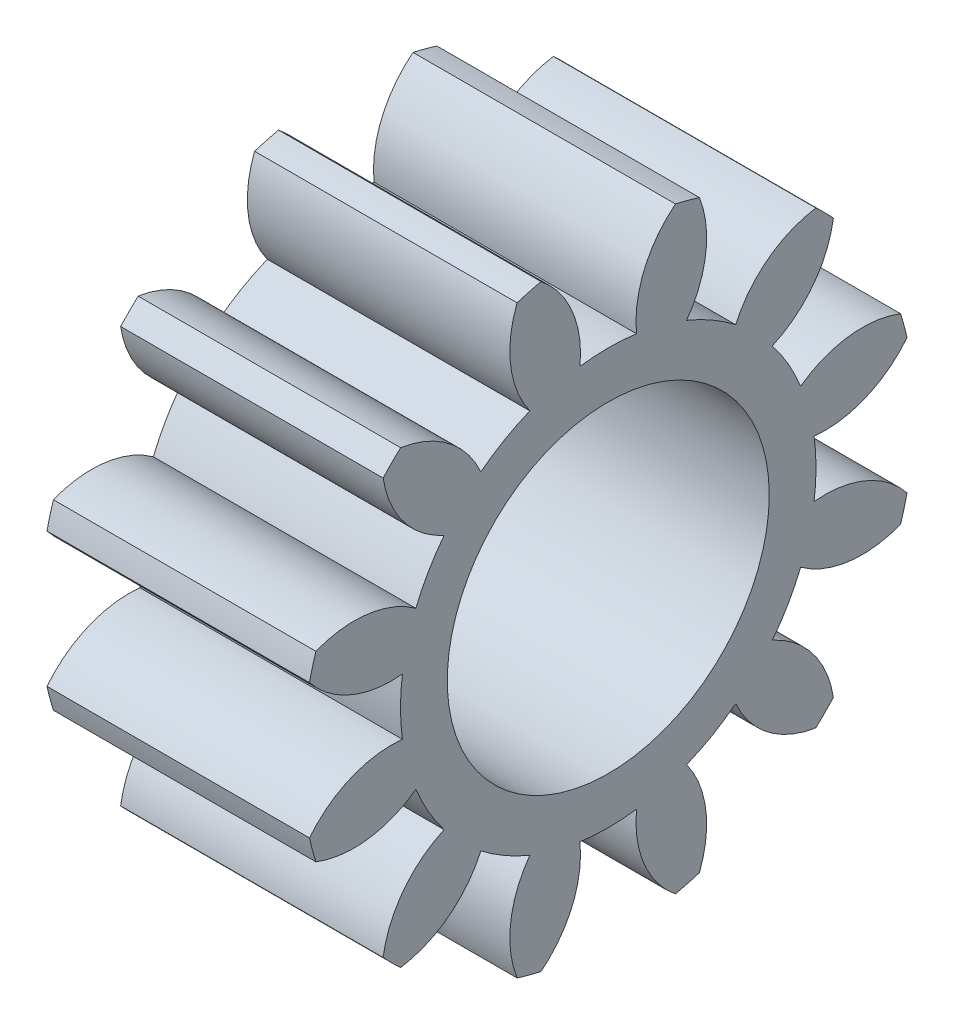
SolidWorks part; units mm, degrees
ref_plane "Plane1" through (0, 0, 0) normal (0, 0, 1) x (1, 0, 0)
ref_plane "Plane2" through (0, 0, 0) normal (0, 1, 0) x (1, 0, 0)
ref_plane "Plane3" through (0, 0, 0) normal (1, 0, 0) x (0, 0, -1)
sketch "HoldingSke" plane through (0, 0, 0) normal (0, 1, 0) x (1, 0, 0)
  line L0 (0, 0) -> (397.5192, -84.4953)
  line L1 (-15, 0) -> (100, 0) construction
  line L2 (0, 0) -> (-2.1039, 2.3779)
  line L3 (0, 0) -> (-11.863, 4.5341)
  line L4 (0, 0) -> (8.4473, 1.7955)
  line L5 (0, 0) -> (-47.5972, -17.7524)
  line L6 (0, 0) -> (-7.8959, -5.3274)
  line L7 (-2.1039, 2.3779) -> (8.8308, 51.9871)
  line L8 (-76.2, 54.61) -> (-69.596, 54.61)
  line L9 (-67.7845, 28.3722) -> (-49.3413, 33.142)
  line L10 (-76.2, 71.12) -> (104.1128, 71.12)
  line L11 (0, 0) -> (-9.525, 0)
  line L12 (-76.2, 101.6) -> (-76.1428, 101.6)
  line L13 (24.9733, 27.94) -> (52.9518, 28.4284)
  line L14 (24.9733, 27.94) -> (24.9746, 27.94)
  line L15 (24.9733, 27.94) -> (100.4006, 29.5858)
  circle A0 centre (0, 0) radius 3.175
  circle A1 centre (0, 0) radius 7.5394
  circle A2 centre (0, 0) radius 38.1
  circle A3 centre (0, 0) radius 3.175
  dimension "MHD" = 15.0787
  dimension "Hub_dia" = 76.2
  dimension "Bore" = 6.35
  dimension "MBD" = 6.35
  dimension "Num_teeth" = 12
  dimension "Pitch" = 406.4
  dimension "Overall_len" = 50.8
  dimension "Show_teeth" = 12
  dimension "Thickness" = 9.525
  dimension "OAL" = 50.8001
  dimension "T_dim" = 6.604
  dimension "Ap" = 14.5
  dimension "H" = 19.05
  dimension "Pitch_radius" = 180.3128
  dimension "Width" = 9.525
  dimension "Backlash" = 0.0571
  dimension "Addendum_fac" = 1
  dimension "Dedendum_fac" = 1.25
  dimension "Clearance_fac" = 0.25
  dimension "Dedendum_add" = 0.0013
sketch "BasProSke" plane through (0, 0, 0) normal (0, 1, 0) x (1, 0, 0)
  line L0 (-10, 0) -> (60, 0) construction
  line L1 (0, 0) -> (0, 11.1125)
  line L2 (0, 0) -> (9.525, 0)
  line L3 (9.525, 0) -> (9.525, 11.1125)
  line L4 (9.525, 11.1125) -> (0, 11.1125)
  dimension "Thickness" = 9.525
  dimension "Diameter" = 22.225
revolve "Base-Revolve" add sketch "BasProSke" angle 360 about L0
sketch "TooCutSke" plane through (0, 0, 0) normal (1, 0, 0) x (0, 0, -1)
  line L1 (0, 0) -> (0, 107) construction
  line L2 (0, 0) -> (-1.3431, 9.4298) construction
  line L3 (0, 0) -> (-4.8949, 18.2679) construction
  line L4 (-1.3431, 9.4298) -> (-2.4474, 9.1339) construction
  arc A0 (1.0269, 7.4691) -> (-1.0269, 7.4691) centre (0, 0) ccw
  arc A1 (2.4651, 10.8617) -> (-2.4651, 10.8617) centre (0, 0) ccw
  circle A2 centre (0, 0) radius 9.525 construction
  circle A3 centre (0, 0) radius 9.2216 construction
  arc A4 (-1.0269, 7.4691) -> (-2.4651, 10.8617) centre (-4.8164, 7.8638) ccw
  arc A5 (2.4651, 10.8617) -> (1.0269, 7.4691) centre (4.8164, 7.8638) ccw
  dimension "Root_dia" = 15.0787
  dimension "Overcut_dia" = 22.2758
  dimension "Pitch_dia" = 19.05
  dimension "Base_dia" = 18.4432
  dimension "Flank_rad" = 3.81
  dimension "Half_ang" = 15
  dimension "Half_CT" = 1.1432
extrude "ToothCut" cut sketch "TooCutSke" along normal through all
fillet "Breaks" [suppressed] radius 0.0318
fillet "RootFillets" [suppressed] radius 0.3981
pattern_circular "TeethCuts" count 12 every 30 about axis through (-10, 0, 0) along (1, 0, 0) of "ToothCut", "RootFillets", "Breaks"
sketch "HubNeaOneSke" plane through (0, 0, 0) normal (-1, 0, 0) x (0, 0, 1)
  circle A0 centre (0, 0) radius 7.5394
  dimension "Diameter" = 15.0787
extrude "HubNearOne" [suppressed] add sketch "HubNeaOneSke" along normal blind 41.2751
sketch "HubNeaBotSke" plane through (0, 0, 0) normal (-1, 0, 0) x (0, 0, 1)
  circle A0 centre (0, 0) radius 7.5394
  dimension "Diameter" = 15.0787
extrude "HubNearBoth" [suppressed] add sketch "HubNeaBotSke" along normal blind 20.6375
ref_plane "FarPln" through (9.525, 0, 0) normal (1, 0, 0) x (0, 0, -1)
sketch "HubFarSke" plane through (9.525, 0, 0) normal (1, 0, 0) x (0, 0, -1)
  circle A0 centre (0, 0) radius 7.5394
  dimension "Diameter" = 15.0787
extrude "HubFar" [suppressed] add sketch "HubFarSke" along normal blind 20.6375
sketch "BorSke" plane through (0, 0, 0) normal (1, 0, 0) x (0, 0, -1)
  circle A0 centre (0, 0) radius 3.175
  dimension "Diameter" = 6.35
extrude "Bore" cut sketch "BorSke" along normal mid plane 101.6001
sketch "KeySke" plane through (0, 0, 0) normal (1, 0, 0) x (0, 0, -1)
  line L0 (-0.127, 0) -> (-0.127, 3.429)
  line L1 (-0.127, 3.429) -> (0.127, 3.429)
  line L2 (0.127, 3.429) -> (0.127, 0)
  line L3 (0, 0) -> (0, 34) construction
  line L4 (-0.127, 0) -> (0.127, 0)
  dimension "Offset" = 3.429
  dimension "Width" = 0.254
extrude "Keyway" [suppressed] cut sketch "KeySke" along normal mid plane 101.6001
pattern_circular "Keyway2" [suppressed] count 2 every 90 about axis through (-10, 0, 0) along (1, 0, 0)
sketch "Sketch1" plane through (0, 0, 0) normal (1, 0, 0) x (0, 0, -1)
  circle A0 centre (0, 0) radius 9.525 construction
  dimension "D1" = 19.05
sketch "Sketch2" plane through (9.525, 0, 0) normal (1, 0, 0) x (0, 0, -1)
  circle A0 centre (0, 0) radius 5.842
  dimension "D1" = 11.684
extrude "Cut-Extrude1" cut sketch "Sketch2" against normal through all
equation "' \"Pitch@HoldingSke\" = 4"
equation "' \"Num_teeth@HoldingSke\" = 12"
equation "' \"Ap@HoldingSke\" =  20"
equation "' \"Ap@HoldingSke\" = 20"
equation "' \"Width@HoldingSke\" = 0.5"
equation "' \"Hub_dia@HoldingSke\"= 1"
equation "' \"Hub_dia@HoldingSke\" = 1"
equation "' \"Overall_len@HoldingSke\" = 1.0"
equation "' \"Bore@HoldingSke\" = 0.75"
equation "' \"T_dim@HoldingSke\" = 0.85"
equation "' \"Width@KeySke\" = 0.25"
equation "' \"Show_teeth@HoldingSke\" = 13"
equation "' \"Backlash@HoldingSke\" = 0.009"
equation "' \"Addendum_fac@HoldingSke\" = 1.0"
equation "' \"Dedendum_fac@HoldingSke\" = 1.25"
equation "' \"Dedendum_add@HoldingSke\" = 0.00005"
equation "' \"Clearance_fac@HoldingSke\" = 0.25"
equation "' \"Pitch@HoldingSke\" = 0.5"
equation "' \"Num_teeth@HoldingSke\" = 23"
equation "' \"Show_teeth@HoldingSke\" = 23"
equation "' \"Backlash@HoldingSke\" = 0.0375"
equation "\"Overcut_dia@TooCutSke\" = (\"Num_teeth@HoldingSke\" + 2 * \"Addendum_fac@HoldingSke\") / \"Pitch@HoldingSke\" + 0.002"
equation "\"Pitch_dia@TooCutSke\" = \"Num_teeth@HoldingSke\" / \"Pitch@HoldingSke\""
equation "\"Base_dia@TooCutSke\" = \"Num_teeth@HoldingSke\" / \"Pitch@HoldingSke\" * cos((\"Ap@HoldingSke\"  * 3.14159265 / 180))"
equation "\"Root_dia@TooCutSke\" = (\"Num_teeth@HoldingSke\" + 2) / \"Pitch@HoldingSke\" - 2 * (\"Addendum_fac@HoldingSke\" + \"Dedendum_fac@HoldingSke\") / \"Pitch@HoldingSke\" - \"Dedendum_add@HoldingSke\" * 2"
equation "\"Half_ang@TooCutSke\" = 180 / \"Num_teeth@HoldingSke\""
equation "\"Half_CT@TooCutSke\" = \"Num_teeth@HoldingSke\" / \"Pitch@HoldingSke\" * sin((3.14159265 / 2 / \"Num_teeth@HoldingSke\")) / 2 - 7 * \"Backlash@HoldingSke\" / 4"
equation "\"Flank_rad@TooCutSke\" = \"Num_teeth@HoldingSke\" / \"Pitch@HoldingSke\" / 5"
equation "\"Radius@RootFillets\" = \"Clearance_fac@HoldingSke\" / \"Pitch@HoldingSke\" + \"Dedendum_add@HoldingSke\""
equation "\"Break_rad@Breaks\" = 0.02 / \"Pitch@HoldingSke\""
equation "\"Thickness@HoldingSke\" = \"Width@HoldingSke\""
equation "\"OAL@HoldingSke\" = \"Thickness@HoldingSke\""
equation "\"MHD@HoldingSke\" = (\"Num_teeth@HoldingSke\" + 2) / \"Pitch@HoldingSke\" - 2 * (\"Addendum_fac@HoldingSke\" + \"Dedendum_fac@HoldingSke\")  / \"Pitch@HoldingSke\" - \"Dedendum_add@HoldingSke\" * 2"
equation "\"MBD@HoldingSke\" = (\"Num_teeth@HoldingSke\" + 2) / \"Pitch@HoldingSke\" - 2 * (\"Addendum_fac@HoldingSke\" + \"Dedendum_fac@HoldingSke\")  / \"Pitch@HoldingSke\" - \"Dedendum_add@HoldingSke\" * 2 - 0.002"
equation "\"MHD@HoldingSke\" = ((sgn( \"MHD@HoldingSke\" - \"Hub_dia@HoldingSke\" )-1)*( \"MHD@HoldingSke\" - \"Hub_dia@HoldingSke\" ))/-2+ \"Hub_dia@HoldingSke\""
equation "\"MBD@HoldingSke\" = ((sgn( \"MBD@HoldingSke\" - \"Bore@HoldingSke\" )-1)*( \"MBD@HoldingSke\" - \"Bore@HoldingSke\" ))/-2+ \"Bore@HoldingSke\""
equation "\"OAL@HoldingSke\" = ((sgn( \"OAL@HoldingSke\" - \"Overall_len@HoldingSke\" )+1)*( \"OAL@HoldingSke\" - \"Overall_len@HoldingSke\" ))/2 + \"Overall_len@HoldingSke\" + 0.000002"
equation "\"Num_teeth@TeethCuts\" = int( \"Show_teeth@HoldingSke\" ) + 1"
equation "\"Num_teeth@TeethCuts\" = ((sgn( \"Num_teeth@TeethCuts\" - \"Num_teeth@HoldingSke\" )-1)*( \"Num_teeth@TeethCuts\" - \"Num_teeth@HoldingSke\" ))/-2+ \"Num_teeth@HoldingSke\""
equation "\"Num_teeth@TeethCuts\" = ((sgn( \"Num_teeth@TeethCuts\" - 2.0)+1)*( \"Num_teeth@TeethCuts\" - 2.0))/2 +2.0"
equation "\"Angle@TeethCuts\" = 360.0 / \"Num_teeth@HoldingSke\""
equation "\"Diameter@BasProSke\" = (\"Num_teeth@HoldingSke\" + 2 * \"Addendum_fac@HoldingSke\") / \"Pitch@HoldingSke\""
equation "\"Thickness@BasProSke\"  = \"Thickness@HoldingSke\""
equation "' \"Fillet_rad@BasProSke\" =  \"Thickness@HoldingSke\" * 0.05"
equation "' \"Fillet_rad@BasProSke\" = \"Thickness@HoldingSke\" * 0.05"
equation "\"MHD@HoldingSke\" = ((sgn( \"MHD@HoldingSke\" - \"Root_dia@TooCutSke\" )-1)*( \"MHD@HoldingSke\" - \"Root_dia@TooCutSke\" ))/-2+ \"Root_dia@TooCutSke\""
equation "\"Diameter@HubNeaOneSke\" = \"MHD@HoldingSke\""
equation "\"Length@HubNearOne\" = \"OAL@HoldingSke\" - \"Thickness@BasProSke\""
equation "\"Diameter@HubNeaBotSke\" = \"MHD@HoldingSke\""
equation "\"Length@HubNearBoth\" = ( \"OAL@HoldingSke\" - \"Thickness@BasProSke\" ) / 2.0"
equation "\"Thickness@FarPln\" = \"Thickness@BasProSke\""
equation "\"Diameter@HubFarSke\" = \"MHD@HoldingSke\""
equation "\"Length@HubFar\" = ( \"OAL@HoldingSke\" - \"Thickness@BasProSke\" ) / 2.0"
equation "\"Diameter@BorSke\" = \"MBD@HoldingSke\""
equation "\"D1@Bore\" = \"OAL@HoldingSke\" * 2.0"
equation "\"D1@Keyway\" = \"OAL@HoldingSke\" * 2.0"
equation "\"Offset@KeySke\" = \"T_dim@HoldingSke\" - \"MBD@HoldingSke\" / 2.0"
